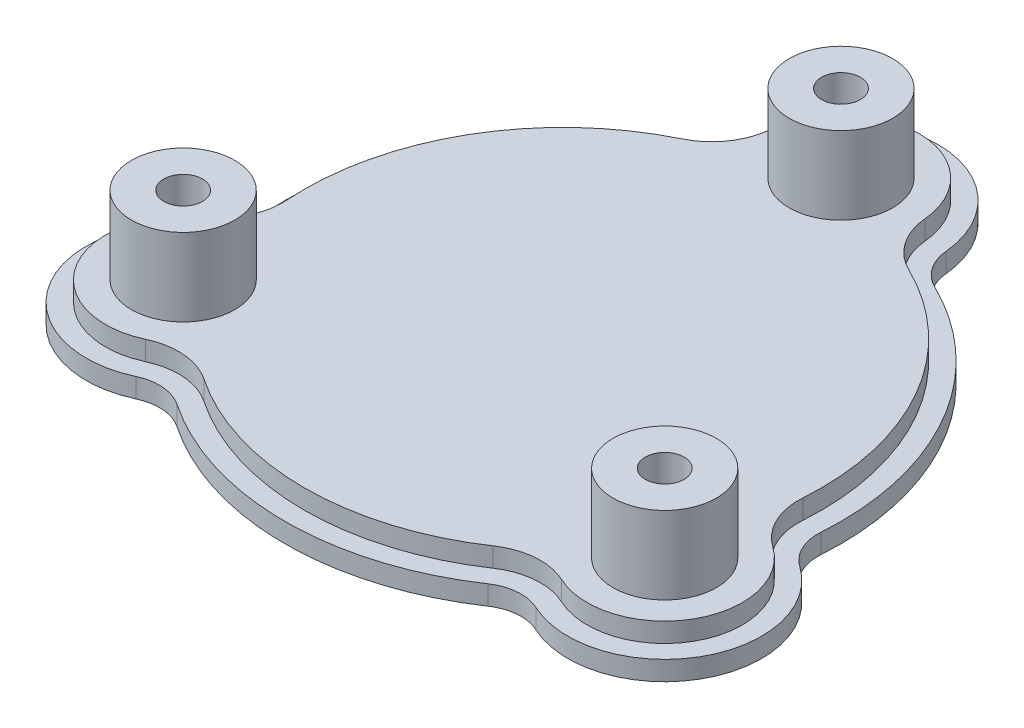
SolidWorks part; units mm, degrees
ref_plane "Front Plane" through (0, 0, 0) normal (0, 0, 1) x (1, 0, 0)
ref_plane "Top Plane" through (0, 0, 0) normal (0, 1, 0) x (1, 0, 0)
ref_plane "Right Plane" through (0, 0, 0) normal (1, 0, 0) x (0, 0, -1)
sketch "Sketch1" plane through (0, 0, 0) normal (0, 1, 0) x (1, 0, 0)
  line L0 (0, 0) -> (0, 37)
  line L1 (0, 0) -> (-32.0429, -18.5)
  line L2 (0, 0) -> (32.0429, -18.5)
  arc A0 (-18.8462, 38.65) -> (-42.895, -3.0038) centre (0, 0) ccw
  circle A1 centre (0, 43) radius 6
  circle A2 centre (0, 43) radius 3
  arc A3 (14.9415, 44.324) -> (-14.9415, 44.324) centre (0, 43) ccw
  arc A4 (14.9415, 44.324) -> (18.8462, 38.65) centre (21.9141, 44.9419) ccw
  arc A5 (-14.9415, 44.324) -> (-18.8462, 38.65) centre (-21.9141, 44.9419) cw
  arc A6 (30.915, -35.1017) -> (24.0488, -35.6462) centre (27.9637, -41.4491) ccw
  arc A7 (45.8564, -9.2223) -> (42.895, -3.0038) centre (49.8779, -3.4927) cw
  circle A8 centre (37.2391, -21.5) radius 3
  circle A9 centre (37.2391, -21.5) radius 6
  arc A10 (45.8564, -9.2223) -> (30.915, -35.1017) centre (37.2391, -21.5) cw
  arc A11 (-45.8564, -9.2223) -> (-42.895, -3.0038) centre (-49.8779, -3.4927) ccw
  arc A12 (-30.915, -35.1017) -> (-24.0488, -35.6462) centre (-27.9637, -41.4491) cw
  circle A13 centre (-37.2391, -21.5) radius 3
  circle A14 centre (-37.2391, -21.5) radius 6
  arc A15 (-30.915, -35.1017) -> (-45.8564, -9.2223) centre (-37.2391, -21.5) cw
  arc A16 (42.895, -3.0038) -> (18.8462, 38.65) centre (0, 0) ccw
  arc A18 (-24.0488, -35.6462) -> (24.0488, -35.6462) centre (0, 0) ccw
  dimension "D1" = 86
  dimension "D2" = 30
  dimension "D3" = 12
  dimension "D4" = 6
  dimension "D5" = 7
  dimension "D6" = 7
extrude "Boss-Extrude2" add sketch "Sketch1" along normal blind 3
sketch "Sketch3" plane through (0, 3, 0) normal (0, 1, 0) x (1, 0, 0)
  arc A0 (11.9532, 44.0592) -> (-11.9532, 44.0592) centre (0, 43) ccw
  arc A1 (-17.5313, 35.9535) -> (-11.9532, 44.0592) centre (-21.9141, 44.9419) ccw
  arc A2 (-17.5313, 35.9535) -> (-39.9023, -2.7942) centre (0, 0) ccw
  arc A3 (-44.133, -11.6779) -> (-39.9023, -2.7942) centre (-49.8779, -3.4927) ccw
  arc A4 (-44.133, -11.6779) -> (-32.1798, -32.3813) centre (-37.2391, -21.5) ccw
  arc A5 (-22.371, -33.1593) -> (-32.1798, -32.3813) centre (-27.9637, -41.4491) ccw
  arc A6 (-22.371, -33.1593) -> (22.371, -33.1593) centre (0, 0) ccw
  arc A7 (32.1798, -32.3813) -> (22.371, -33.1593) centre (27.9637, -41.4491) ccw
  arc A8 (32.1798, -32.3813) -> (44.133, -11.6779) centre (37.2391, -21.5) ccw
  arc A9 (39.9023, -2.7942) -> (44.133, -11.6779) centre (49.8779, -3.4927) ccw
  arc A10 (39.9023, -2.7942) -> (17.5313, 35.9535) centre (0, 0) ccw
  arc A11 (11.9532, 44.0592) -> (17.5313, 35.9535) centre (21.9141, 44.9419) ccw
  arc A12 (-24.0488, -35.6462) -> (-30.915, -35.1017) centre (-27.9637, -41.4491) ccw
  arc A13 (-24.0488, -35.6462) -> (24.0488, -35.6462) centre (0, 0) ccw
  arc A14 (30.915, -35.1017) -> (24.0488, -35.6462) centre (27.9637, -41.4491) ccw
  arc A15 (30.915, -35.1017) -> (45.8564, -9.2223) centre (37.2391, -21.5) ccw
  arc A16 (42.895, -3.0038) -> (45.8564, -9.2223) centre (49.8779, -3.4927) ccw
  arc A17 (42.895, -3.0038) -> (18.8462, 38.65) centre (0, 0) ccw
  arc A18 (14.9415, 44.324) -> (18.8462, 38.65) centre (21.9141, 44.9419) ccw
  arc A19 (14.9415, 44.324) -> (-14.9415, 44.324) centre (0, 43) ccw
  arc A20 (-18.8462, 38.65) -> (-14.9415, 44.324) centre (-21.9141, 44.9419) ccw
  arc A21 (-18.8462, 38.65) -> (-42.895, -3.0038) centre (0, 0) ccw
  arc A22 (-45.8564, -9.2223) -> (-42.895, -3.0038) centre (-49.8779, -3.4927) ccw
  arc A23 (-45.8564, -9.2223) -> (-30.915, -35.1017) centre (-37.2391, -21.5) ccw
  arc A24 (-24.0488, -35.6462) -> (-30.915, -35.1017) centre (-27.9637, -41.4491) ccw
  arc A25 (-24.0488, -35.6462) -> (24.0488, -35.6462) centre (0, 0) ccw
  arc A26 (30.915, -35.1017) -> (24.0488, -35.6462) centre (27.9637, -41.4491) ccw
  arc A27 (30.915, -35.1017) -> (45.8564, -9.2223) centre (37.2391, -21.5) ccw
  arc A28 (42.895, -3.0038) -> (45.8564, -9.2223) centre (49.8779, -3.4927) ccw
  arc A29 (42.895, -3.0038) -> (18.8462, 38.65) centre (0, 0) ccw
  arc A30 (14.9415, 44.324) -> (18.8462, 38.65) centre (21.9141, 44.9419) ccw
  arc A31 (14.9415, 44.324) -> (-14.9415, 44.324) centre (0, 43) ccw
  arc A32 (-18.8462, 38.65) -> (-14.9415, 44.324) centre (-21.9141, 44.9419) ccw
  arc A33 (-18.8462, 38.65) -> (-42.895, -3.0038) centre (0, 0) ccw
  arc A34 (-45.8564, -9.2223) -> (-42.895, -3.0038) centre (-49.8779, -3.4927) ccw
  arc A35 (-45.8564, -9.2223) -> (-30.915, -35.1017) centre (-37.2391, -21.5) ccw
  circle A36 centre (37.2391, -21.5) radius 6 construction
  circle A37 centre (-37.2391, -21.5) radius 6 construction
  circle A38 centre (0, 43) radius 6 construction
  circle A39 centre (37.2391, -21.5) radius 6
  circle A40 centre (-37.2391, -21.5) radius 6
  circle A41 centre (0, 43) radius 6
  circle A42 centre (0, 43) radius 8
  circle A43 centre (37.2391, -21.5) radius 8
  circle A44 centre (-37.2391, -21.5) radius 8
  dimension "D1" = 0
  dimension "D2" = 3
extrude "Boss-Extrude4" add sketch "Sketch3" along normal blind 3 contours A0 A1 A2 A3 A4 A5 A6 A7 A8 A9 A10 A11 | A40 | A41 | A39
sketch "Sketch6" plane through (0, 6, 0) normal (0, 1, 0) x (1, 0, 0)
  circle A1 centre (0, 43) radius 8
  circle A2 centre (37.2391, -21.5) radius 8
  circle A3 centre (-37.2391, -21.5) radius 8
  circle A5 centre (0, 43) radius 6
  circle A6 centre (37.2391, -21.5) radius 6
  circle A7 centre (-37.2391, -21.5) radius 6
  arc A12 (11.9532, 44.0592) -> (17.5313, 35.9535) centre (21.9141, 44.9419) ccw
  arc A13 (11.9532, 44.0592) -> (-11.9532, 44.0592) centre (0, 43) ccw
  arc A14 (-17.5313, 35.9535) -> (-11.9532, 44.0592) centre (-21.9141, 44.9419) ccw
  arc A15 (-17.5313, 35.9535) -> (-39.9023, -2.7942) centre (0, 0) ccw
  arc A16 (-44.133, -11.6779) -> (-39.9023, -2.7942) centre (-49.8779, -3.4927) ccw
  arc A17 (-44.133, -11.6779) -> (-32.1798, -32.3813) centre (-37.2391, -21.5) ccw
  arc A18 (-22.371, -33.1593) -> (-32.1798, -32.3813) centre (-27.9637, -41.4491) ccw
  arc A19 (-22.371, -33.1593) -> (22.371, -33.1593) centre (0, 0) ccw
  arc A20 (32.1798, -32.3813) -> (22.371, -33.1593) centre (27.9637, -41.4491) ccw
  arc A21 (32.1798, -32.3813) -> (44.133, -11.6779) centre (37.2391, -21.5) ccw
  arc A22 (39.9023, -2.7942) -> (44.133, -11.6779) centre (49.8779, -3.4927) ccw
  arc A23 (39.9023, -2.7942) -> (17.5313, 35.9535) centre (0, 0) ccw
  arc A24 (11.9532, 44.0592) -> (17.5313, 35.9535) centre (21.9141, 44.9419) ccw
  arc A25 (11.9532, 44.0592) -> (-11.9532, 44.0592) centre (0, 43) ccw
  arc A26 (-17.5313, 35.9535) -> (-11.9532, 44.0592) centre (-21.9141, 44.9419) ccw
  arc A27 (-17.5313, 35.9535) -> (-39.9023, -2.7942) centre (0, 0) ccw
  arc A28 (-44.133, -11.6779) -> (-39.9023, -2.7942) centre (-49.8779, -3.4927) ccw
  arc A29 (-44.133, -11.6779) -> (-32.1798, -32.3813) centre (-37.2391, -21.5) ccw
  arc A30 (-22.371, -33.1593) -> (-32.1798, -32.3813) centre (-27.9637, -41.4491) ccw
  arc A31 (-22.371, -33.1593) -> (22.371, -33.1593) centre (0, 0) ccw
  arc A32 (32.1798, -32.3813) -> (22.371, -33.1593) centre (27.9637, -41.4491) ccw
  arc A33 (32.1798, -32.3813) -> (44.133, -11.6779) centre (37.2391, -21.5) ccw
  arc A34 (39.9023, -2.7942) -> (44.133, -11.6779) centre (49.8779, -3.4927) ccw
  arc A35 (39.9023, -2.7942) -> (17.5313, 35.9535) centre (0, 0) ccw
  circle M13 centre (0, 43) radius 6
  circle M26 centre (-37.2391, -21.5) radius 6
  circle M27 centre (37.2391, -21.5) radius 6
  dimension "D1" = 0
extrude "Boss-Extrude6" add sketch "Sketch6" along normal blind 6 contours A1 M13 | A3 M26 | A2 M27
sketch "Sketch7" plane through (0, 12, 0) normal (0, 1, 0) x (1, 0, 0)
  circle A0 centre (37.2391, -21.5) radius 6 construction
  circle A1 centre (0, 43) radius 8
  circle A2 centre (0, 43) radius 8
  circle A3 centre (37.2391, -21.5) radius 6
  circle A4 centre (0, 43) radius 6 construction
  circle A5 centre (37.2391, -21.5) radius 8 construction
  circle A6 centre (-37.2391, -21.5) radius 6 construction
  circle A7 centre (-37.2391, -21.5) radius 8 construction
  circle A8 centre (0, 43) radius 6
  circle A9 centre (37.2391, -21.5) radius 8
  circle A10 centre (-37.2391, -21.5) radius 6
  circle A11 centre (-37.2391, -21.5) radius 8
  circle A12 centre (0, 43) radius 3
  circle A13 centre (37.2391, -21.5) radius 3
  circle A14 centre (-37.2391, -21.5) radius 3
  circle M4 centre (0, 43) radius 6
  circle M5 centre (0, 43) radius 8
  dimension "D1" = 0
extrude "Boss-Extrude7" add sketch "Sketch7" along normal blind 6 contours M5 M4 | A12 M4 | A11 A10 | A10 A14 | A3 A13 | A9 A3
